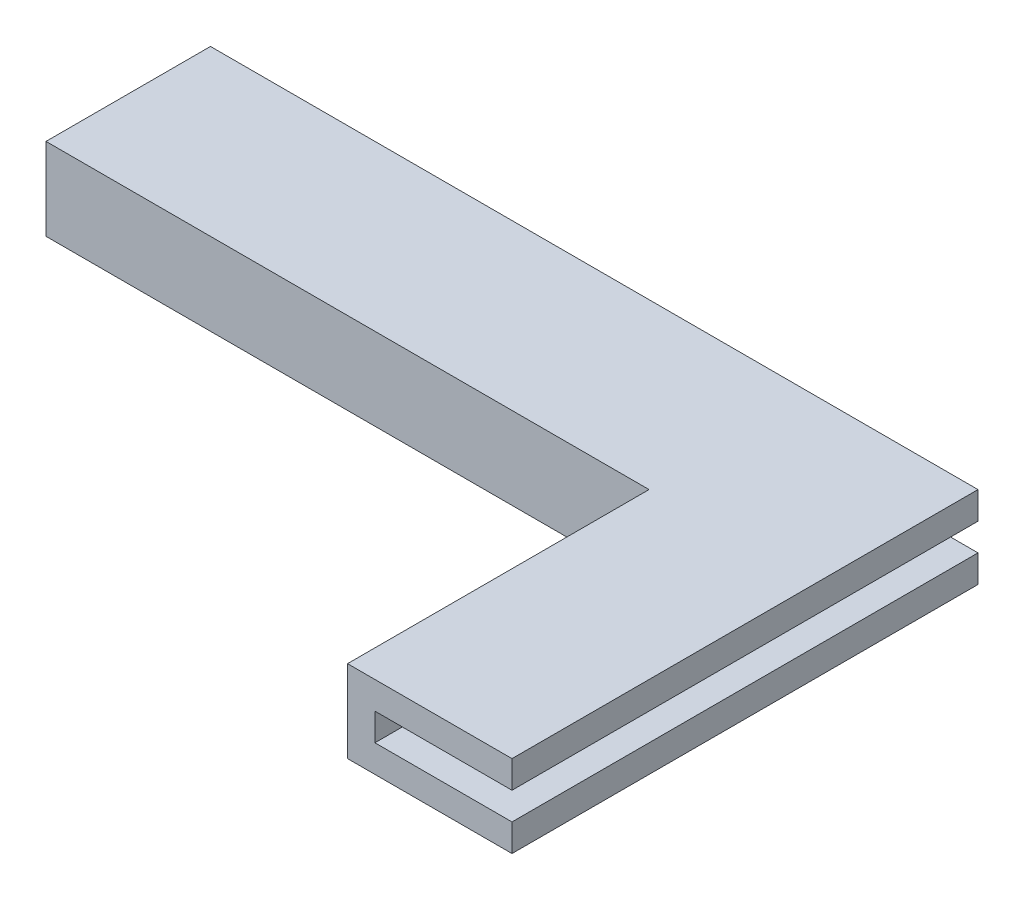
SolidWorks part; units mm, degrees
ref_plane "Front Plane" through (0, 0, 0) normal (0, 0, 1) x (1, 0, 0)
ref_plane "Top Plane" through (0, 0, 0) normal (0, 1, 0) x (1, 0, 0)
ref_plane "Right Plane" through (0, 0, 0) normal (1, 0, 0) x (0, 0, -1)
sketch "Sketch1" plane through (0, 0, 0) normal (0, 0, 1) x (1, 0, 0)
  line L0 (28, 2) -> (28, 1) construction
  line L1 (0, 0) -> (28, 0)
  line L2 (0, 0) -> (0, 1)
  line L3 (0, 1) -> (28, 1)
  line L4 (28, 0) -> (28, 1)
  line L5 (0, 2) -> (28, 2)
  line L6 (0, 2) -> (0, 3)
  line L7 (0, 3) -> (28, 3)
  line L8 (28, 2) -> (28, 3)
  dimension "D1" = 28
  dimension "D2" = 1
extrude "Boss-Extrude1" add sketch "Sketch1" along normal blind 5
sketch "Sketch2" plane through (0, 0, 5) normal (0, 0, 1) x (1, 0, 0)
  line L0 (0, 0) -> (28, 0) construction
  line L1 (0, 3) -> (28, 3)
  line L2 (0, 3) -> (0, 0)
  line L3 (0, 0) -> (28, 0)
  line L5 (28, 2) -> (28, 3) construction
  line L6 (28, 3) -> (0, 3) construction
  line L7 (28, 0) -> (28, 1)
  line L8 (28, 1) -> (23, 1)
  line L9 (28, 1) -> (0, 1) construction
  line L10 (23, 1) -> (23, 2)
  line L11 (0, 2) -> (28, 2) construction
  line L12 (23, 2) -> (28, 2)
  line L13 (28, 2) -> (28, 3)
  dimension "D1" = 5
extrude "Boss-Extrude2" add sketch "Sketch2" along normal blind 1
sketch "Sketch3" plane through (0, 0, 6) normal (0, 0, 1) x (1, 0, 0)
  line L0 (28, 3) -> (22, 3)
  line L1 (28, 3) -> (0, 3) construction
  line L2 (22, 3) -> (22, 0)
  line L3 (0, 0) -> (28, 0) construction
  line L4 (22, 0) -> (28, 0)
  line L5 (28, 0) -> (28, 1)
  line L6 (28, 1) -> (23, 1)
  line L7 (23, 1) -> (23, 2)
  line L8 (23, 2) -> (28, 2)
  line L9 (28, 3) -> (28, 2)
  dimension "D1" = 1
extrude "Boss-Extrude3" add sketch "Sketch3" along normal blind 11
